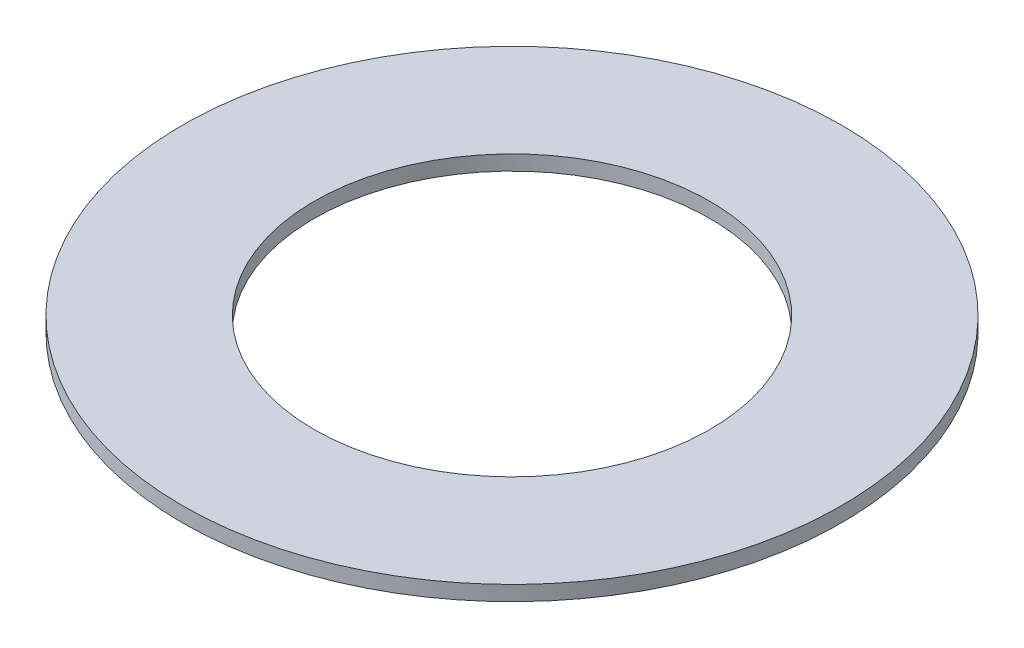
SolidWorks part; units mm, degrees
ref_plane "Front Plane" through (0, 0, 0) normal (0, 0, 1) x (1, 0, 0)
ref_plane "Top Plane" through (0, 0, 0) normal (0, 1, 0) x (1, 0, 0)
ref_plane "Right Plane" through (0, 0, 0) normal (1, 0, 0) x (0, 0, -1)
sketch "Sketch1" plane through (0, 0, 0) normal (0, 1, 0) x (1, 0, 0)
  circle A0 centre (0, 0) radius 66.2477
  circle A1 centre (0, 0) radius 39.7621
extrude "Boss-Extrude1" add sketch "Sketch1" along normal blind 3
